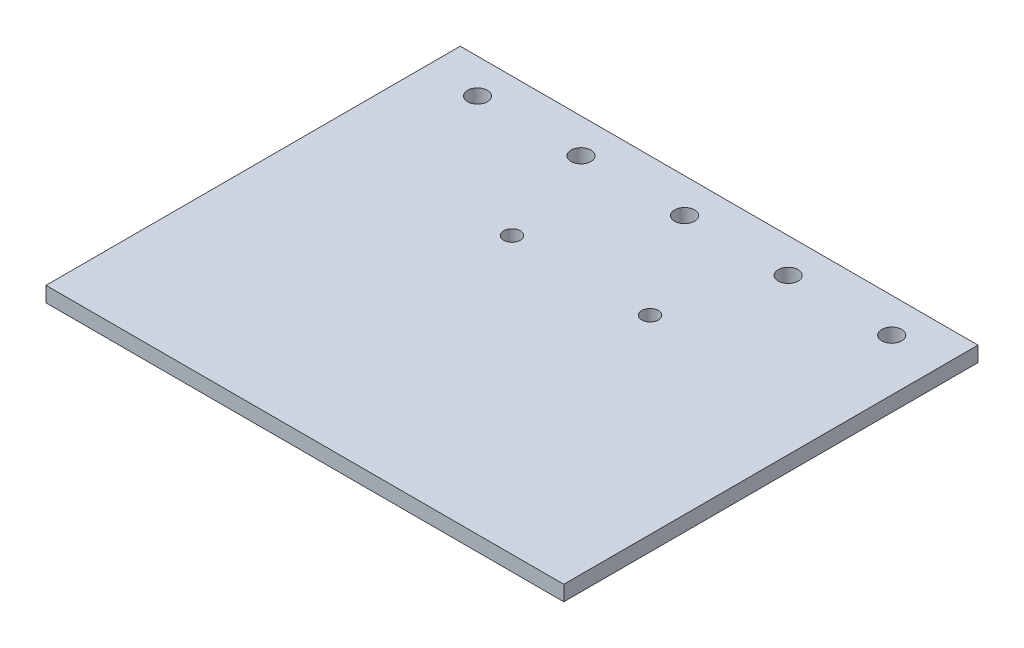
SolidWorks part; units mm, degrees
material "Acrylic (Medium-high impact)"
ref_plane "Front" through (0, 0, 0) normal (0, 0, 1) x (1, 0, 0)
ref_plane "Top" through (0, 0, 0) normal (0, 1, 0) x (1, 0, 0)
ref_plane "Right" through (0, 0, 0) normal (1, 0, 0) x (0, 0, -1)
sketch "Sketch1" plane through (0, 0, 0) normal (0, 1, 0) x (1, 0, 0)
  line L1 (-47.625, 38.1) -> (47.625, 38.1)
  line L2 (-47.625, 38.1) -> (-47.625, -38.1)
  line L3 (-47.625, -38.1) -> (47.625, -38.1)
  line L4 (47.625, 38.1) -> (47.625, -38.1)
  line L5 (-47.625, 38.1) -> (47.625, -38.1) construction
  line L6 (-47.625, -38.1) -> (47.625, 38.1) construction
  point P0 (0, 0)
  dimension "D1" = 95.25
  dimension "D2" = 76.2
extrude "Boss-Extrude1" add sketch "Sketch1" along normal blind 2.794
sketch "Sketch2" plane through (0, 2.794, 0) normal (0, 1, 0) x (1, 0, 0)
  line L0 (0, 0) -> (0, 38.1) construction
  line L1 (47.625, 38.1) -> (-47.625, 38.1) construction
  line L2 (-38.1, 31.75) -> (0, 31.75) construction
  line L3 (0, 31.75) -> (38.1, 31.75) construction
  circle A0 centre (-38.1, 31.75) radius 1.8288
  circle A1 centre (-19.05, 31.75) radius 1.8288
  circle A2 centre (0, 31.75) radius 1.8288
  circle A3 centre (19.05, 31.75) radius 1.8288
  circle A4 centre (38.1, 31.75) radius 1.8288
  dimension "D3" = 3.6576
  dimension "D1" = 76.2
  dimension "D2" = 6.35
extrude "Cut-Extrude1" cut sketch "Sketch2" against normal through all
sketch "Sketch3" plane through (0, 2.794, 0) normal (0, 1, 0) x (1, 0, 0)
  line L0 (0, -38.1) -> (0, 12.7) construction
  line L1 (-47.625, -38.1) -> (47.625, -38.1) construction
  line L2 (-12.7, 12.7) -> (12.7, 12.7) construction
  circle A0 centre (-12.7, 12.7) radius 1.524
  circle A1 centre (12.7, 12.7) radius 1.524
  dimension "D3" = 3.048
  dimension "D1" = 25.4
  dimension "D2" = 50.8
extrude "Cut-Extrude2" cut sketch "Sketch3" against normal through all
